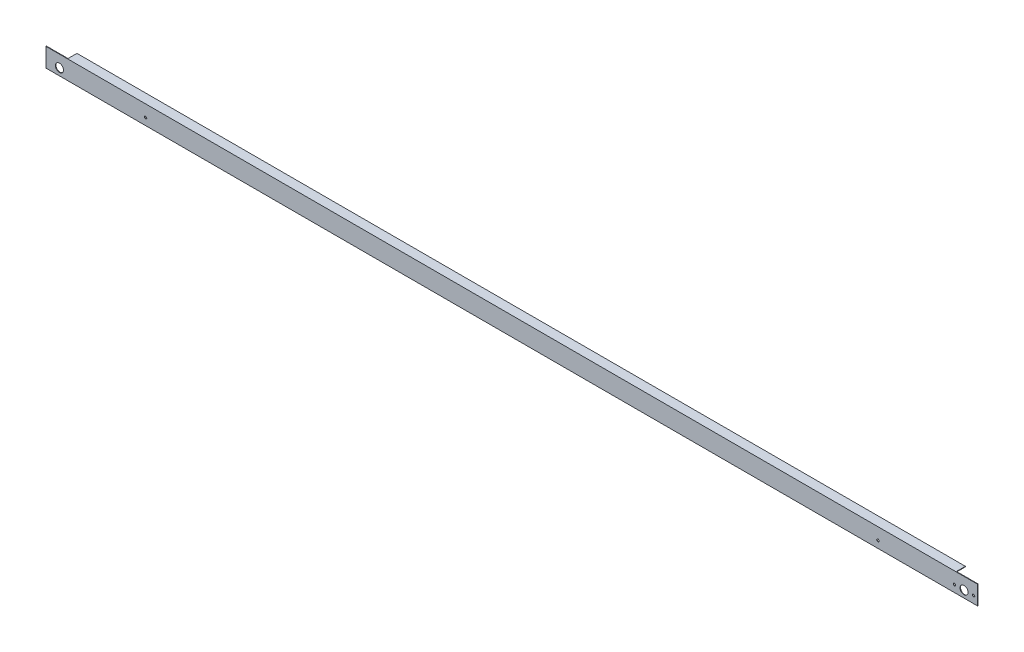
SolidWorks part; units mm, degrees
material "Galvanized Steel"
ref_plane "Front Plane" through (0, 0, 0) normal (0, 0, 1) x (1, 0, 0)
ref_plane "Top Plane" through (0, 0, 0) normal (0, 1, 0) x (1, 0, 0)
ref_plane "Right Plane" through (0, 0, 0) normal (1, 0, 0) x (0, 0, -1)
sketch "Sketch1" plane through (0, 0, 0) normal (1, 0, 0) x (0, 0, -1)
  line L0 (0, 0) -> (0, 63.5)
  line L1 (0, 63.5) -> (44.45, 63.5)
  line L4 (2.3813, 0) -> (2.3813, 61.1187)
  line L5 (2.3813, 61.1187) -> (44.45, 61.1187)
  line L6 (44.45, 63.5) -> (44.45, 61.1187)
  line L8 (0, 0) -> (0, -25.4)
  line L12 (0, 0) -> (0, -10.3249) construction
  line L13 (2.3813, 0) -> (2.3813, -10.3249) construction
  line L14 (2.3813, -25.4) -> (2.3813, 0)
  line L15 (0, -25.4) -> (2.3813, -25.4)
  dimension "D1" = 63.5
  dimension "D2" = 44.45
  dimension "D3" = 25.4
  dimension "D6" = 2.3813
extrude "Boss-Extrude1" add sketch "Sketch1" along normal blind 4394.2
sketch "Sketch2" plane through (0, 0, -2.3813) normal (0, 0, -1) x (-1, 0, 0)
  line L0 (-4394.2, 63.5) -> (0, 63.5) construction
  line L1 (-4394.2, -25.4) -> (-4394.2, 61.1187) construction
  line L2 (0, -25.4) -> (0, 61.1187) construction
  circle A0 centre (-4330.7, 7.62) radius 19.05
  circle A1 centre (-63.5, 7.62) radius 19.05
  circle A2 centre (-4285.6547, 7.62) radius 5.5562
  circle A3 centre (-4375.7453, 7.62) radius 5.5562
  dimension "D1" = 38.1
  dimension "D4" = 38.1
  dimension "D7" = 11.1125
  dimension "D8" = 45.0453
  dimension "D2" = 55.88
  dimension "D3" = 63.5
  dimension "D5" = 55.88
  dimension "D6" = 63.5
  dimension "D9" = 45.0453
extrude "Cut-Extrude1" cut sketch "Sketch2" against normal up to next
sketch "Sketch3" plane through (0, 0, -2.3813) normal (0, 0, -1) x (-1, 0, 0)
  line L19 (-4394.2, 61.1187) -> (0, 61.1187) construction
  line L20 (-4394.2, 63.5) -> (-4292.6, 63.5)
  line L21 (-4394.2, 63.5) -> (-4394.2, 61.1187)
  line L22 (-4394.2, 61.1187) -> (-4292.6, 61.1187)
  line L23 (-4292.6, 63.5) -> (-4292.6, 61.1187)
  line L25 (0, 63.5) -> (-101.6, 63.5)
  line L26 (0, 63.5) -> (0, 61.1187)
  line L27 (0, 61.1187) -> (-101.6, 61.1187)
  line L28 (-101.6, 63.5) -> (-101.6, 61.1187)
  dimension "D1" = 101.6
  dimension "D2" = 101.6
extrude "Cut-Extrude4" cut sketch "Sketch3" along normal up to next
sketch "Sketch4" plane through (0, 0, -2.3813) normal (0, 0, -1) x (-1, 0, 0)
  line L0 (-469.9, 7.62) -> (-3924.3, 7.62) construction
  line L1 (-4292.6, 63.5) -> (-101.6, 63.5) construction
  circle A13 centre (-3924.3, 7.62) radius 5.588
  circle A14 centre (-469.9, 7.62) radius 5.588
  circle A15 centre (-63.5, 7.62) radius 19.05 construction
  circle A16 centre (-63.5, 7.62) radius 19.05
  point P5 (-2197.1, 7.62)
  point P11 (-2197.1, 63.5)
  dimension "D2" = 406.4
  dimension "D1" = 11.176
extrude "Cut-Extrude5" cut sketch "Sketch4" against normal up to next (2.3813 mm away)
